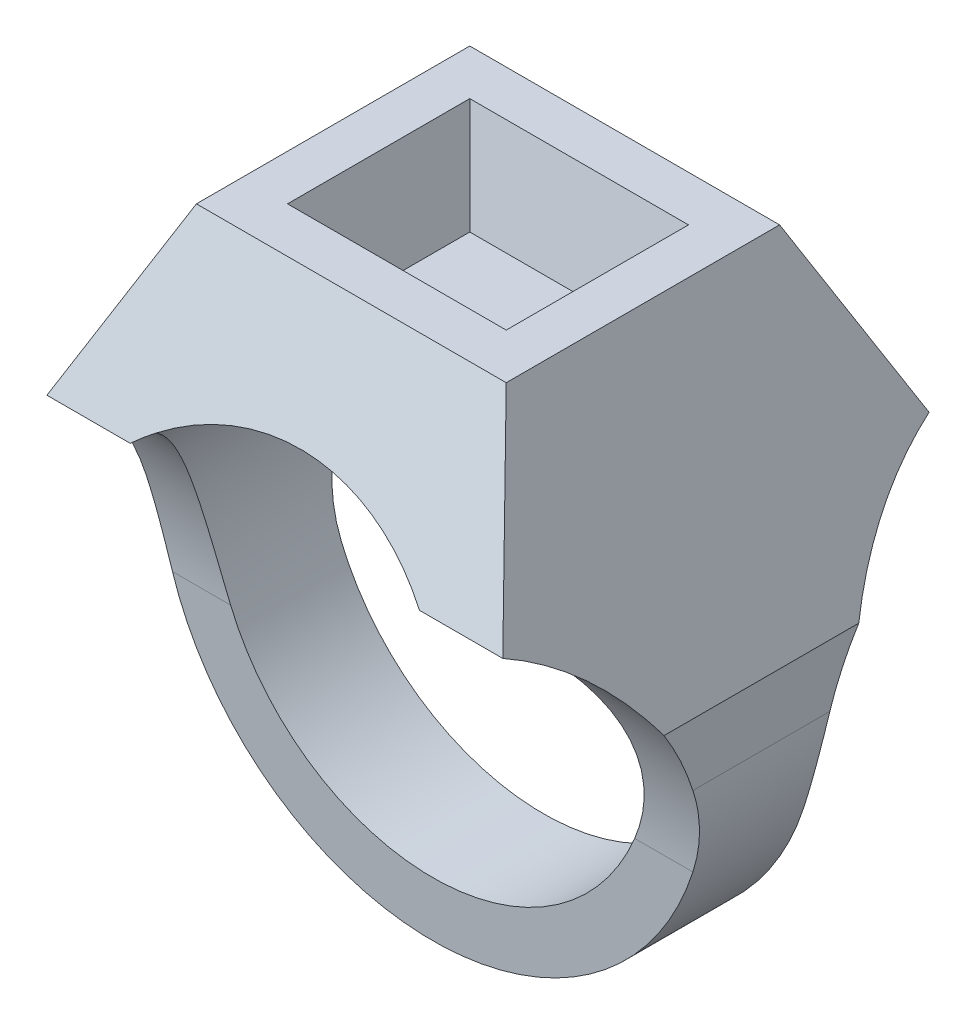
SolidWorks part; units mm, degrees
ref_plane "前视基准面" through (0, 0, 0) normal (0, 0, 1) x (1, 0, 0)
ref_plane "上视基准面" through (0, 0, 0) normal (0, 1, 0) x (1, 0, 0)
ref_plane "右视基准面" through (0, 0, 0) normal (1, 0, 0) x (0, 0, -1)
other "Configuration Table"
sketch "草图1" plane through (0, 0, 0) normal (0, 0, 1) x (1, 0, 0)
  line L0 (-8.5, 18) -> (8.5, 18)
  line L1 (-8.5, 18) -> (-15, 3.4008)
  line L2 (0, 0) -> (0, 27.4163) construction
  line L3 (8.5, 18) -> (15, 3.4008)
  line L4 (-15, 0) -> (-15, 3.4008)
  line L5 (15, 0) -> (15, 3.4008)
  circle A0 centre (0, 0) radius 12
  arc A1 (-15, 0) -> (15, 0) centre (0, 0) ccw
  point P8 (0, 18)
  dimension "D1" = 24
  dimension "D2" = 30
  dimension "D3" = 66
  dimension "D4" = 17
  dimension "D5" = 18
extrude "凸台-拉伸1" add sketch "草图1" along normal mid plane 50
sketch "草图2" plane through (0, 0, 0) normal (1, 0, 0) x (0, 0, -1)
  line L0 (-7.5, 18) -> (7.5, 18)
  line L1 (-25, 18) -> (25, 18) construction
  line L2 (7.5, 18) -> (11.6968, 9)
  line L3 (3.036, -4.5946) -> (3.036, -15)
  line L4 (-25, -15) -> (25, -15) construction
  line L5 (0, 0) -> (0, -10.1502) construction
  line L6 (-3.036, -4.5946) -> (-3.036, -15)
  line L7 (-7.5, 18) -> (-11.6968, 9)
  line L8 (-3.036, -15) -> (3.036, -15)
  arc A0 (11.6968, 9) -> (3.036, -4.5946) centre (18.036, -4.5946) ccw
  arc A1 (-11.6968, 9) -> (-3.036, -4.5946) centre (-18.036, -4.5946) cw
  point P5 (0, 18)
  dimension "D1" = 15
  dimension "D3" = 15
  dimension "D2" = 65
  dimension "D4" = 9
extrude "切除-拉伸1" cut sketch "草图2" against normal through all both and the other way through all flip side to cut
sketch "草图3" plane through (0, 18, 0) normal (0, 1, 0) x (1, 0, 0)
  line L1 (-6, -5) -> (6, -5)
  line L2 (-6, -5) -> (-6, 5)
  line L3 (-6, 5) -> (6, 5)
  line L4 (6, -5) -> (6, 5)
  line L5 (-6, -5) -> (6, 5) construction
  line L6 (-6, 5) -> (6, -5) construction
  point P0 (0, 0)
  dimension "D1" = 10
  dimension "D2" = 12
extrude "切除-拉伸2" cut sketch "草图3" against normal blind 5 draft 15 and the other way through all
